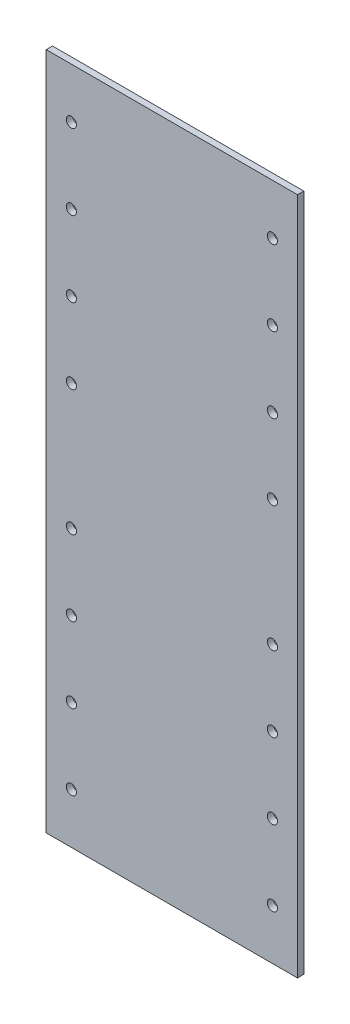
SolidWorks part; units mm, degrees
ref_plane "Front Plane" through (0, 0, 0) normal (0, 0, 1) x (1, 0, 0)
ref_plane "Top Plane" through (0, 0, 0) normal (0, 1, 0) x (1, 0, 0)
ref_plane "Right Plane" through (0, 0, 0) normal (1, 0, 0) x (0, 0, -1)
sketch "Sketch1" plane through (0, 0, 0) normal (0, 0, 1) x (1, 0, 0)
  line L1 (-63.5, -171.45) -> (63.5, -171.45)
  line L2 (-63.5, -171.45) -> (-63.5, 171.45)
  line L3 (-63.5, 171.45) -> (63.5, 171.45)
  line L4 (63.5, -171.45) -> (63.5, 171.45)
  line L5 (-63.5, -171.45) -> (63.5, 171.45) construction
  line L6 (-63.5, 171.45) -> (63.5, -171.45) construction
  point P0 (0, 0)
  dimension "D1" = 342.9
  dimension "D2" = 127
extrude "Boss-Extrude1" add sketch "Sketch1" along normal blind 3.175
sketch "Sketch2" plane through (0, 0, 3.175) normal (0, 0, 1) x (1, 0, 0)
  line L0 (-50.8, 171.45) -> (-50.8, -171.45) construction
  line L1 (63.5, 171.45) -> (-63.5, 171.45) construction
  line L2 (-63.5, -171.45) -> (63.5, -171.45) construction
  line L3 (-63.5, 171.45) -> (-63.5, -171.45) construction
  circle A0 centre (-50.8, -146.05) radius 2.5797
  circle A1 centre (-50.8, -107.95) radius 2.5797
  circle A2 centre (-50.8, -69.85) radius 2.5797
  circle A3 centre (-50.8, 69.85) radius 2.5797
  circle A4 centre (-50.8, 107.95) radius 2.5797
  circle A5 centre (-50.8, 146.05) radius 2.5797
  circle A6 centre (-50.8, 31.75) radius 2.5797
  circle A7 centre (-50.8, -31.75) radius 2.5797
  dimension "D1" = 5.1594
  dimension "D3" = 25.4
  dimension "D4" = 38.1
  dimension "D5" = 38.1
  dimension "D6" = 25.4
  dimension "D7" = 38.1
  dimension "D8" = 38.1
  dimension "D9" = 38.1
  dimension "D10" = 38.1
  dimension "D2" = 12.7
extrude "Cut-Extrude1" cut sketch "Sketch2" against normal blind 3.175
ref_plane "Plane1" through (0, 0, 0) normal (1, 0, 0) x (0, 0, -1)
mirror "Mirror1" about plane through (0, 0, 0) normal (1, 0, 0) of "Cut-Extrude1"
